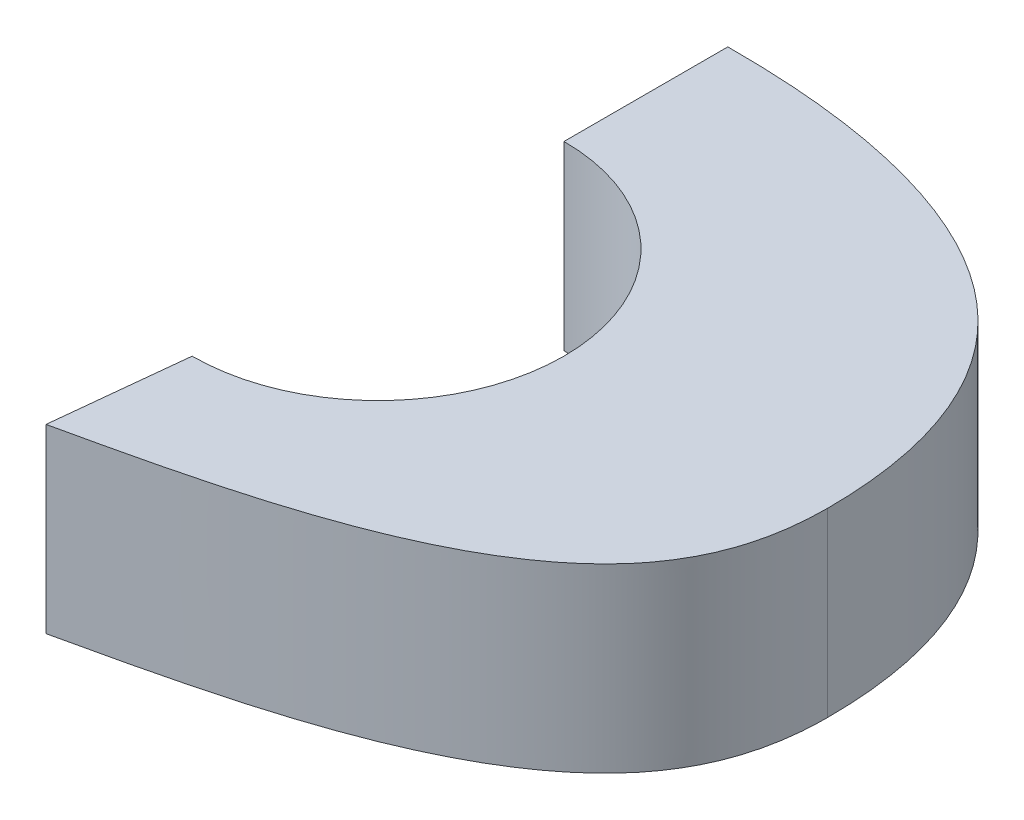
SolidWorks part; units mm, degrees
ref_plane "Front Plane" through (0, 0, 0) normal (0, 0, 1) x (1, 0, 0)
ref_plane "Top Plane" through (0, 0, 0) normal (0, 1, 0) x (1, 0, 0)
ref_plane "Right Plane" through (0, 0, 0) normal (1, 0, 0) x (0, 0, -1)
sketch "Sketch1" plane through (0, 0, 0) normal (0, 1, 0) x (1, 0, 0)
  line L0 (0, 0) -> (29.8, 0) construction
  line L1 (0, 0) -> (0, 24.3) construction
  line L2 (0, 0) -> (0, -22.5) construction
  line L3 (0, 0) -> (-86.5, 0) construction
  line L4 (-26, 0) -> (-26, 24.3) construction
  line L5 (-86.5, 0) -> (-86.5, 37.2) construction
  line L6 (-86.5, 11.6) -> (-124.6, 11.6) construction
  line L7 (-86.5, 0) -> (-86.5, -27.9) construction
  dimension "D1" = 29.8
  dimension "D2" = 24.3
  dimension "D3" = 22.5
  dimension "D4" = 26
  dimension "D5" = 86.5
  dimension "D6" = 27.9
  dimension "D7" = 37.2
  dimension "D8" = 11.6
  dimension "D9" = 38.1
sketch "Sketch2" plane through (0, 0, 0) normal (0, 1, 0) x (1, 0, 0)
  line L0 (-26, 24.3) -> (0, 24.3)
  line L1 (-124.6, 0.1449) -> (-124.6, 23.0551) construction
  line L2 (-106.5667, 37.2) -> (-66.4333, 37.2) construction
  line L3 (-42.2984, 24.3) -> (-9.7006, 24.3) construction
  line L4 (-107.4998, 37.2) -> (-65.4572, 37.2) construction
  line L5 (-64.2941, -27.9) -> (-108.7059, -27.9) construction
  line L6 (29.8, -11.2792) -> (29.8, 11.2792) construction
  line L7 (29.8, -14.0147) -> (29.8, 14.0918) construction
  spline S0 degree 3 poles (-26, 24.3) (-46.3736, 24.3) (-60.2234, 37.2) (-86.5, 37.2) knots 0 0 0 0 1 1 1 1
  spline S1 degree 3 poles (-86.5, 37.2) (-111.5833, 37.2) (-124.6, 21.1459) (-124.6, 11.6) knots 0 0 0 0 1 1 1 1
  spline S2 degree 3 poles (0, 24.3) (20.6838, 24.3847) (29.8, 14.099) (29.8, 0) knots 0 0 0 0 1 1 1 1
  spline S3 degree 3 poles (29.8, 0) (29.8, -15.9034) (12.7938, -19.6737) (0, -22.5) knots 0 0 0 0 1 1 1 1
  spline S4 degree 2 poles (-86.5, -27.9) (-58.7426, -27.9) (0, -22.5) knots 0 0 0 1 1 1
  spline S5 degree 3 poles (-124.6, 11.6) (-126.6455, -15.9296) (-96.1692, -28.4589) (-86.5, -27.9) knots 0 0 0 0 1 1 1 1
  point P0 (0, 24.3)
  point P2 (29.8, 0)
  point P4 (0, -22.5)
  point P6 (-26, 24.3)
  point P8 (-86.5, 37.2)
  point P10 (-124.6, 11.6)
  point P12 (-86.5, -27.9)
extrude "Boss-Extrude1" add sketch "Sketch2" along normal blind 10
sketch "Sketch5" plane through (0, 10, 0) normal (0, 1, 0) x (1, 0, 0)
  line L2 (0, 19.3) -> (-26, 19.3)
  line L3 (0, 19.3) -> (-26, 19.3)
  line L4 (-133.1401, 55.1699) -> (57.5258, 55.1699)
  line L5 (-133.1401, 55.1699) -> (-133.1401, -43.745)
  line L6 (-133.1401, -43.745) -> (57.5258, -43.745)
  line L7 (57.5258, 55.1699) -> (57.5258, -43.745)
  spline S10 degree 3 poles (794.3178, 2896.6346) (236.5633, 295.2684) (75.1344, 4.3942) (-36.2999, 20.219) (-38.8232, 20.7499) (-43.8284, 22.0533) (-46.3131, 22.8262) (-51.2444, 24.4704) (-53.694, 25.3411) (-58.6071, 27.0407) (-61.0707, 27.8688) (-64.8063, 28.9893) (-66.0595, 29.343) (-68.5722, 29.9962) (-69.8324, 30.2958) (-73.6263, 31.1023) (-76.1734, 31.5152) (-394.4154, 65.5197) (-1008.6606, -1988.9699) (-1423.0021, -2645.3199) knots -5.207716 -5.207716 -5.207716 -5.207716 0.125 0.125 0.25 0.25 0.375 0.375 0.5 0.5 0.625 0.625 0.6875 0.6875 0.75 0.75 0.875 0.875 16.247306 16.247306 16.247306 16.247306 only from (-26, 19.3) to (-86.5, 32.2)
  spline S11 degree 3 poles (-155.0275, 3009.7498) (283.9644, -579.3508) (39.2092, 61.7589) (-97.8181, 30.8894) (-98.6695, 30.6698) (-100.363, 30.1729) (-101.2079, 29.8946) (-103.7072, 28.973) (-105.3145, 28.249) (-108.4025, 26.5648) (-109.8852, 25.604) (-112.6954, 23.4124) (-113.9894, 22.2093) (-115.7364, 20.2177) (-116.2861, 19.5225) (-117.3076, 18.0567) (-117.7719, 17.2971) (-118.3806, 16.1123) (-118.5688, 15.7095) (-118.9104, 14.8853) (-119.0639, 14.463) (-119.321, 13.6124) (-119.4258, 13.1825) (-119.5345, 12.528) (-119.5626, 12.3083) (-119.5889, 11.9755) (-119.595, 11.8641) (-119.8529, 2.1663) (-91.4737, -13.0524) (-3067.996, 562.8701) knots -9.69525 -9.69525 -9.69525 -9.69525 0.25 0.25 0.3125 0.3125 0.375 0.375 0.5 0.5 0.625 0.625 0.75 0.75 0.8125 0.8125 0.875 0.875 0.90625 0.90625 0.9375 0.9375 0.96875 0.96875 0.984375 0.984375 0.992188 0.992188 1.660503 1.660503 1.660503 1.660503 only from (-86.5, 32.2) to (-119.6, 11.4145)
  spline S12 degree 3 poles (-3114.144, -159.344) (-75.3215, 65.211) (-118.2824, 36.1888) (-119.6695, 10.3135) (-119.7026, 9.4894) (-119.7017, 8.668) (-119.6533, 7.0291) (-119.5587, 5.9417) (-119.3168, 4.3187) (-119.2195, 3.7791) (-118.9903, 2.7027) (-118.8578, 2.164) (-118.4114, 0.5683) (-118.0496, -0.4661) (-117.2048, -2.4791) (-116.7219, -3.4578) (-115.911, -4.8862) (-115.6263, -5.3557) (-115.0287, -6.2817) (-114.7151, -6.739) (-113.0981, -8.9672) (-111.6366, -10.5868) (-109.2434, -12.8211) (-108.4118, -13.5331) (-107.1168, -14.5549) (-106.6765, -14.8883) (-105.787, -15.5353) (-105.3374, -15.8493) (-103.0661, -17.3743) (-101.1758, -18.4523) (-98.2376, -19.8702) (-97.2408, -20.3092) (-95.21, -21.1148) (-94.1746, -21.4822) (-92.0643, -22.1268) (-91.001, -22.402) (-89.3879, -22.7093) (-88.8471, -22.7942) (-88.0288, -22.8795) (-87.7547, -22.9009) (-87.3409, -22.9165) (-87.2025, -22.919) (-75.8543, -22.7912) (-57.6729, 17.6935) (-565.1077, -2984.244) knots -1.438804 -1.438804 -1.438804 -1.438804 0.015625 0.015625 0.03125 0.0625 0.0625 0.125 0.125 0.15625 0.15625 0.1875 0.1875 0.25 0.25 0.3125 0.3125 0.34375 0.34375 0.375 0.375 0.5 0.5 0.5625 0.5625 0.59375 0.59375 0.625 0.625 0.75 0.75 0.8125 0.8125 0.875 0.875 0.9375 0.9375 0.96875 0.96875 0.984375 0.984375 0.992187 0.992187 1.621629 1.621629 1.621629 1.621629 only from (-119.6, 11.4145) to (-86.6438, -22.9)
  spline S13 degree 3 poles (-743.0619, 2883.7324) (-404.1471, 44.7095) (-237.6226, -27.3739) (-72.2929, -22.6309) (-68.7098, -22.4892) (-57.9653, -21.9864) (-50.8087, -21.5494) (-36.5025, -20.5633) (-29.353, -20.0121) (442.1069, 18.8609) (896.2577, 220.25) (1524.6058, -2374.3013) knots -5.513822 -5.513822 -5.513822 -5.513822 0.125 0.125 0.25 0.25 0.5 0.5 0.75 0.75 16.991268 16.991268 16.991268 16.991268 only from (-86.6438, -22.9) to (-0.7711, -17.5498)
  spline S14 degree 3 poles (684.9632, -2932.2413) (-188.4077, 55.2091) (-72.0811, -37.5503) (8.73, -15.2186) (10.0645, -14.8145) (12.6997, -13.9014) (14.0008, -13.3934) (15.9119, -12.5052) (16.5421, -12.1879) (17.7844, -11.497) (18.3919, -11.1257) (19.5594, -10.3246) (20.1212, -9.8941) (20.9205, -9.1892) (21.1807, -8.9434) (21.6785, -8.4347) (21.9161, -8.1719) (22.5926, -7.3563) (22.9947, -6.7761) (23.5131, -5.8423) (23.6718, -5.5198) (23.9536, -4.8681) (24.0777, -4.5373) (24.4029, -3.5305) (24.5567, -2.8403) (31.3062, 45.0348) (-209.6675, 121.1409) (2725.17, -1306.3496) knots -7.13592 -7.13592 -7.13592 -7.13592 0.25 0.25 0.375 0.375 0.5 0.5 0.5625 0.5625 0.625 0.625 0.6875 0.6875 0.71875 0.71875 0.75 0.75 0.8125 0.8125 0.84375 0.84375 0.875 0.875 0.9375 0.9375 5.110249 5.110249 5.110249 5.110249 only from (-0.7711, -17.5498) to (24.8, 0)
  spline S15 degree 3 poles (3003.4514, 307.3213) (-329.5265, -207.9997) (38.0399, -68.0338) (24.2703, 5.1555) (24.0952, 5.8744) (23.7648, 6.9407) (23.6433, 7.2941) (23.3755, 7.9966) (23.2292, 8.3451) (22.7584, 9.3658) (22.3999, 10.019) (21.5892, 11.2682) (21.1362, 11.865) (19.6347, 13.56) (18.4892, 14.5137) (16.9097, 15.5257) (16.5854, 15.7195) (15.9298, 16.0859) (15.5982, 16.2589) (14.5926, 16.7499) (13.9081, 17.0401) (12.5153, 17.5579) (11.807, 17.7854) (10.3698, 18.1863) (9.6387, 18.36) (7.4366, 18.806) (5.959, 19.0045) (-85.4866, 26.721) (-201.9485, -238.1682) (23.3888, 3011.2925) knots -6.115667 -6.115667 -6.115667 -6.115667 0.125 0.125 0.1875 0.1875 0.21875 0.21875 0.25 0.25 0.3125 0.3125 0.375 0.375 0.5 0.5 0.53125 0.53125 0.5625 0.5625 0.625 0.625 0.6875 0.6875 0.75 0.75 0.875 0.875 8.448739 8.448739 8.448739 8.448739 only from (24.8, 0) to (0, 19.3)
  spline S16 degree 3 poles (-26, 19.3) (-28.6144, 19.3) (-31.1955, 19.4941) (-36.2999, 20.219) (-38.8232, 20.7499) (-43.8284, 22.0533) (-46.3131, 22.8262) (-51.2444, 24.4704) (-53.694, 25.3411) (-58.6071, 27.0407) (-61.0707, 27.8688) (-64.8063, 28.9893) (-66.0595, 29.343) (-68.5722, 29.9962) (-69.8324, 30.2958) (-73.6263, 31.1023) (-76.1734, 31.5152) (-81.3072, 32.0638) (-83.8939, 32.2) (-86.5, 32.2) knots 0 0 0 0 0.125 0.125 0.25 0.25 0.375 0.375 0.5 0.5 0.625 0.625 0.6875 0.6875 0.75 0.75 0.875 0.875 1 1 1 1
  spline S17 degree 3 poles (-86.5, 32.2) (-90.0477, 32.2) (-93.5393, 31.8534) (-97.8181, 30.8894) (-98.6695, 30.6698) (-100.363, 30.1729) (-101.2079, 29.8946) (-103.7072, 28.973) (-105.3145, 28.249) (-108.4025, 26.5648) (-109.8852, 25.604) (-112.6954, 23.4124) (-113.9894, 22.2093) (-115.7364, 20.2177) (-116.2861, 19.5225) (-117.3076, 18.0567) (-117.7719, 17.2971) (-118.3806, 16.1123) (-118.5688, 15.7095) (-118.9104, 14.8853) (-119.0639, 14.463) (-119.321, 13.6124) (-119.4258, 13.1825) (-119.5345, 12.528) (-119.5626, 12.3083) (-119.5889, 11.9755) (-119.595, 11.8641) (-119.6009, 11.64) (-119.6, 11.5271) (-119.6, 11.4145) knots 0 0 0 0 0.25 0.25 0.3125 0.3125 0.375 0.375 0.5 0.5 0.625 0.625 0.75 0.75 0.8125 0.8125 0.875 0.875 0.90625 0.90625 0.9375 0.9375 0.96875 0.96875 0.984375 0.984375 0.992188 0.992188 1 1 1 1
  spline S18 degree 3 poles (-119.6, 11.4145) (-119.6205, 11.139) (-119.64, 10.8636) (-119.6695, 10.3135) (-119.7026, 9.4894) (-119.7017, 8.668) (-119.6533, 7.0291) (-119.5587, 5.9417) (-119.3168, 4.3187) (-119.2195, 3.7791) (-118.9903, 2.7027) (-118.8578, 2.164) (-118.4114, 0.5683) (-118.0496, -0.4661) (-117.2048, -2.4791) (-116.7219, -3.4578) (-115.911, -4.8862) (-115.6263, -5.3557) (-115.0287, -6.2817) (-114.7151, -6.739) (-113.0981, -8.9672) (-111.6366, -10.5868) (-109.2434, -12.8211) (-108.4118, -13.5331) (-107.1168, -14.5549) (-106.6765, -14.8883) (-105.787, -15.5353) (-105.3374, -15.8493) (-103.0661, -17.3743) (-101.1758, -18.4523) (-98.2376, -19.8702) (-97.2408, -20.3092) (-95.21, -21.1148) (-94.1746, -21.4822) (-92.0643, -22.1268) (-91.001, -22.402) (-89.3879, -22.7093) (-88.8471, -22.7942) (-88.0288, -22.8795) (-87.7547, -22.9009) (-87.3409, -22.9165) (-87.2025, -22.919) (-86.9242, -22.9159) (-86.784, -22.9081) (-86.6438, -22.9) knots 0 0 0 0 0.015625 0.015625 0.03125 0.0625 0.0625 0.125 0.125 0.15625 0.15625 0.1875 0.1875 0.25 0.25 0.3125 0.3125 0.34375 0.34375 0.375 0.375 0.5 0.5 0.5625 0.5625 0.59375 0.59375 0.625 0.625 0.75 0.75 0.8125 0.8125 0.875 0.875 0.9375 0.9375 0.96875 0.96875 0.984375 0.984375 0.992187 0.992187 1 1 1 1
  spline S19 degree 3 poles (-86.6438, -22.9) (-83.0517, -22.9018) (-79.4639, -22.8367) (-72.2929, -22.6309) (-68.7098, -22.4892) (-57.9653, -21.9864) (-50.8087, -21.5494) (-36.5025, -20.5633) (-29.353, -20.0121) (-15.0588, -18.8335) (-7.9141, -18.2056) (-0.7711, -17.5498) knots 0 0 0 0 0.125 0.125 0.25 0.25 0.5 0.5 0.75 0.75 1 1 1 1
  spline S20 degree 3 poles (-0.7711, -17.5498) (1.9633, -16.9454) (4.6953, -16.3336) (8.73, -15.2186) (10.0645, -14.8145) (12.6997, -13.9014) (14.0008, -13.3934) (15.9119, -12.5052) (16.5421, -12.1879) (17.7844, -11.497) (18.3919, -11.1257) (19.5594, -10.3246) (20.1212, -9.8941) (20.9205, -9.1892) (21.1807, -8.9434) (21.6785, -8.4347) (21.9161, -8.1719) (22.5926, -7.3563) (22.9947, -6.7761) (23.5131, -5.8423) (23.6718, -5.5198) (23.9536, -4.8681) (24.0777, -4.5373) (24.4029, -3.5305) (24.5567, -2.8403) (24.756, -1.4273) (24.8, -0.7143) (24.8, 0) knots 0 0 0 0 0.25 0.25 0.375 0.375 0.5 0.5 0.5625 0.5625 0.625 0.625 0.6875 0.6875 0.71875 0.71875 0.75 0.75 0.8125 0.8125 0.84375 0.84375 0.875 0.875 0.9375 0.9375 1 1 1 1
  spline S21 degree 3 poles (24.8, 0) (24.8, 1.4998) (24.6799, 2.9783) (24.2703, 5.1555) (24.0952, 5.8744) (23.7648, 6.9407) (23.6433, 7.2941) (23.3755, 7.9966) (23.2292, 8.3451) (22.7584, 9.3658) (22.3999, 10.019) (21.5892, 11.2682) (21.1362, 11.865) (19.6347, 13.56) (18.4892, 14.5137) (16.9097, 15.5257) (16.5854, 15.7195) (15.9298, 16.0859) (15.5982, 16.2589) (14.5926, 16.7499) (13.9081, 17.0401) (12.5153, 17.5579) (11.807, 17.7854) (10.3698, 18.1863) (9.6387, 18.36) (7.4366, 18.806) (5.959, 19.0045) (2.9895, 19.2551) (1.4975, 19.3061) (0, 19.3) knots 0 0 0 0 0.125 0.125 0.1875 0.1875 0.21875 0.21875 0.25 0.25 0.3125 0.3125 0.375 0.375 0.5 0.5 0.53125 0.53125 0.5625 0.5625 0.625 0.625 0.6875 0.6875 0.75 0.75 0.875 0.875 1 1 1 1
  dimension "D1" = 5
extrude "Cut-Extrude2" cut sketch "Sketch5" against normal through all
sketch "Sketch3" plane through (0, 10, 0) normal (0, 1, 0) x (1, 0, 0)
  line L0 (0, 0) -> (-59.9237, 0) construction
  line L1 (0, 0) -> (-86.5, 0) construction
  line L4 (-136.9811, 47.2597) -> (55.003, 47.2597)
  line L6 (-136.9811, 47.2597) -> (-136.9811, -45.2157)
  line L7 (0, 0) -> (0, 24.3) construction
  line L8 (-136.9811, -45.2157) -> (55.003, -45.2157)
  line L9 (55.003, 47.2597) -> (55.003, -45.2157)
  line L12 (0, 0) -> (0, -22.5) construction
  line L13 (0, 19.3) -> (0, 10.2587)
  line L14 (0, -10.2587) -> (-0.7711, -17.5498)
  arc A0 (0, 10.2587) -> (0, -10.2587) centre (0, 0) cw
  spline S4 degree 3 poles (2014.7792, 157.4755) (-251.7771, -177.4141) (36.5089, -59.896) (24.2703, 5.1555) (24.0952, 5.8744) (23.7648, 6.9407) (23.6433, 7.2941) (23.3755, 7.9966) (23.2292, 8.3451) (22.7584, 9.3658) (22.3999, 10.019) (21.5892, 11.2682) (21.1362, 11.865) (19.6347, 13.56) (18.4892, 14.5137) (16.9097, 15.5257) (16.5854, 15.7195) (15.9298, 16.0859) (15.5982, 16.2589) (14.5926, 16.7499) (13.9081, 17.0401) (12.5153, 17.5579) (11.807, 17.7854) (10.3698, 18.1863) (9.6387, 18.36) (7.4366, 18.806) (5.959, 19.0045) (-75.0154, 25.8374) (-175.1957, -180.1948) (-41.9858, 2013.4713) knots -5.414826 -5.414826 -5.414826 -5.414826 0.125 0.125 0.1875 0.1875 0.21875 0.21875 0.25 0.25 0.3125 0.3125 0.375 0.375 0.5 0.5 0.53125 0.53125 0.5625 0.5625 0.625 0.625 0.6875 0.6875 0.75 0.75 0.875 0.875 7.567171 7.567171 7.567171 7.567171 only from (24.8, 0) to (0, 19.3) construction
  spline S5 degree 3 poles (407.8796, -1971.4254) (-160.6006, 34.3029) (-62.3962, -34.8739) (8.73, -15.2186) (10.0645, -14.8145) (12.6997, -13.9014) (14.0008, -13.3934) (15.9119, -12.5052) (16.5421, -12.1879) (17.7844, -11.497) (18.3919, -11.1257) (19.5594, -10.3246) (20.1212, -9.8941) (20.9205, -9.1892) (21.1807, -8.9434) (21.6785, -8.4347) (21.9161, -8.1719) (22.5926, -7.3563) (22.9947, -6.7761) (23.5131, -5.8423) (23.6718, -5.5198) (23.9536, -4.8681) (24.0777, -4.5373) (24.4029, -3.5305) (24.5567, -2.8403) (30.5346, 39.562) (-157.0824, 103.8698) (1826.5255, -867.8005) knots -6.235759 -6.235759 -6.235759 -6.235759 0.25 0.25 0.375 0.375 0.5 0.5 0.5625 0.5625 0.625 0.625 0.6875 0.6875 0.71875 0.71875 0.75 0.75 0.8125 0.8125 0.84375 0.84375 0.875 0.875 0.9375 0.9375 4.626099 4.626099 4.626099 4.626099 only from (-0.7711, -17.5498) to (24.8, 0) construction
  spline S6 degree 3 poles (24.8, 0) (24.8, 1.4998) (24.6799, 2.9783) (24.2703, 5.1555) (24.0952, 5.8744) (23.7648, 6.9407) (23.6433, 7.2941) (23.3755, 7.9966) (23.2292, 8.3451) (22.7584, 9.3658) (22.3999, 10.019) (21.5892, 11.2682) (21.1362, 11.865) (19.6347, 13.56) (18.4892, 14.5137) (16.9097, 15.5257) (16.5854, 15.7195) (15.9298, 16.0859) (15.5982, 16.2589) (14.5926, 16.7499) (13.9081, 17.0401) (12.5153, 17.5579) (11.807, 17.7854) (10.3698, 18.1863) (9.6387, 18.36) (7.4366, 18.806) (5.959, 19.0045) (2.9895, 19.2551) (1.4975, 19.3061) (0, 19.3) knots 0 0 0 0 0.125 0.125 0.1875 0.1875 0.21875 0.21875 0.25 0.25 0.3125 0.3125 0.375 0.375 0.5 0.5 0.53125 0.53125 0.5625 0.5625 0.625 0.625 0.6875 0.6875 0.75 0.75 0.875 0.875 1 1 1 1
  spline S7 degree 3 poles (-0.7711, -17.5498) (1.9633, -16.9454) (4.6953, -16.3336) (8.73, -15.2186) (10.0645, -14.8145) (12.6997, -13.9014) (14.0008, -13.3934) (15.9119, -12.5052) (16.5421, -12.1879) (17.7844, -11.497) (18.3919, -11.1257) (19.5594, -10.3246) (20.1212, -9.8941) (20.9205, -9.1892) (21.1807, -8.9434) (21.6785, -8.4347) (21.9161, -8.1719) (22.5926, -7.3563) (22.9947, -6.7761) (23.5131, -5.8423) (23.6718, -5.5198) (23.9536, -4.8681) (24.0777, -4.5373) (24.4029, -3.5305) (24.5567, -2.8403) (24.756, -1.4273) (24.8, -0.7143) (24.8, 0) knots 0 0 0 0 0.25 0.25 0.375 0.375 0.5 0.5 0.5625 0.5625 0.625 0.625 0.6875 0.6875 0.71875 0.71875 0.75 0.75 0.8125 0.8125 0.84375 0.84375 0.875 0.875 0.9375 0.9375 1 1 1 1
extrude "Cut-Extrude1" cut sketch "Sketch3" against normal through all
